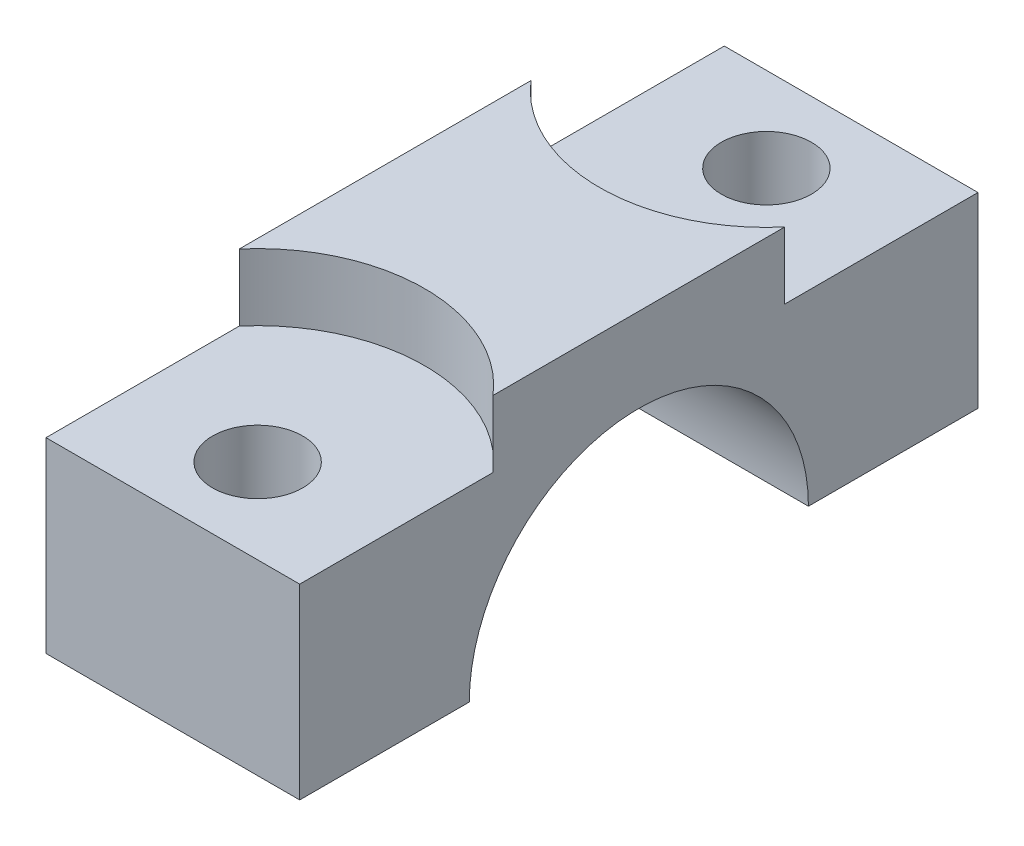
SolidWorks part; units mm, degrees
ref_plane "Front Plane" through (0, 0, 0) normal (0, 0, 1) x (1, 0, 0)
ref_plane "Top Plane" through (0, 0, 0) normal (0, 1, 0) x (1, 0, 0)
ref_plane "Right Plane" through (0, 0, 0) normal (1, 0, 0) x (0, 0, -1)
sketch "Sketch1" plane through (0, 0, 0) normal (1, 0, 0) x (0, 0, -1)
  line L0 (12.7, 0) -> (25.4, 0)
  line L1 (-25.4, 19) -> (25.4, 19)
  line L2 (-25.4, 19) -> (-25.4, 0)
  line L3 (-25.4, 0) -> (-12.7, 0)
  line L4 (25.4, 19) -> (25.4, 0)
  line L5 (-25.4, 19) -> (25.4, 0) construction
  line L6 (-25.4, 0) -> (25.4, 19) construction
  arc A1 (-12.7, 0) -> (12.7, 0) centre (0, 0) cw
  point P0 (0, 9.5)
  point P5 (0, 0)
  point P10 (0, 19)
  point P12 (0, 0)
  dimension "D3" = 12.7
  dimension "D1" = 50.8
  dimension "D2" = 19
extrude "Boss-Extrude1" add sketch "Sketch1" along normal mid plane 19
sketch "Sketch2" plane through (0, 0, 0) normal (0, -1, 0) x (1, 0, 0)
  line L0 (-9.5, 19.05) -> (9.5, 19.05) construction
  line L1 (-9.5, 25.4) -> (-9.5, 12.7) construction
  line L2 (9.5, 25.4) -> (9.5, 12.7) construction
  line L3 (-9.5, -19.05) -> (9.5, -19.05) construction
  line L4 (-9.5, -12.7) -> (-9.5, -25.4) construction
  line L5 (9.5, -12.7) -> (9.5, -25.4) construction
  point P12 (0, -19.05)
  point P13 (0, 19.05)
hole_wizard "CBORE for M12 Hex Head Cap Screw2" positions "Sketch6" profile "Sketch7" counterbore size "M12" standard "ISO" end condition up to next
sketch "Sketch6" plane through (0, 19, 0) normal (0, 1, 0) x (1, 0, 0)
  point P0 (0, 19.05)
  point P3 (0, -19.05)
sketch "Sketch7" plane through (0, 19, -19.05) normal (1, 0, 0) x (0, 0, 1)
  line L0 (0, 0) -> (0, 19)
  line L1 (0, 19) -> (3.375, 19)
  line L3 (3.375, 19) -> (3.375, 5)
  line L4 (3.375, 5) -> (12.5, 5)
  line L5 (12.5, 5) -> (12.5, 0)
  line L7 (12.5, 0) -> (0, 0)
  line L11 (0, -6.35) -> (0, 107.95) construction
  dimension "Thru Hole Dia." = 6.75
  dimension "Thru Hole Depth" = 19
  dimension "C'Bore Dia." = 25
  dimension "C'Bore Depth" = 5
